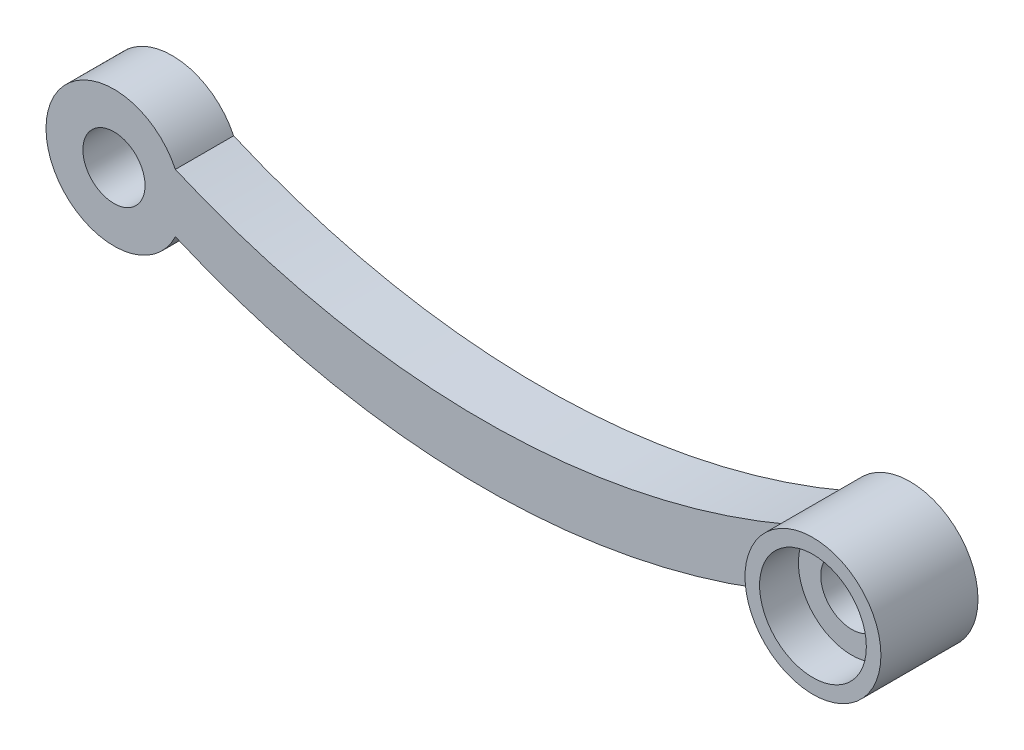
SolidWorks part; units mm, degrees
ref_plane "Front Plane" through (0, 0, 0) normal (0, 0, 1) x (1, 0, 0)
ref_plane "Top Plane" through (0, 0, 0) normal (0, 1, 0) x (1, 0, 0)
ref_plane "Right Plane" through (0, 0, 0) normal (1, 0, 0) x (0, 0, -1)
sketch "Sketch2" plane through (0, 0, 0) normal (0, 0, 1) x (1, 0, 0)
  line L0 (-19, 0) -> (-11.7639, 0) construction
  line L1 (-19, 3.5) -> (19, 3.5) construction
  line L2 (-19, -3.5) -> (19, -3.5) construction
  line L3 (0, 0) -> (0, -3.5) construction
  line L5 (15.8377, -1.5) -> (15.8377, 1.5) construction
  line L7 (-15.8377, -1.5) -> (-15.8377, 1.5) construction
  line L9 (15.8377, 1.5) -> (8.6603, 0.8202) construction
  line L10 (11.7639, 0) -> (19, 0) construction
  line L11 (-8.6603, 0.8202) -> (-15.8377, 1.5) construction
  arc A0 (-19, 3.5) -> (-19, -3.5) centre (-19, 0) ccw construction
  arc A1 (19, -3.5) -> (19, 3.5) centre (19, 0) ccw construction
  arc A2 (-15.8377, 1.5) -> (-15.8377, -1.5) centre (-19, 0) ccw
  circle A3 centre (-19, 0) radius 1.6
  circle A4 centre (19, 0) radius 1.6
  arc A5 (15.8377, 1.5) -> (15.8377, -1.5) centre (19, 0) cw
  arc A8 (-15.8377, -1.5) -> (15.8377, -1.5) centre (0, 35.231) ccw
  arc A9 (-15.8377, 1.5) -> (15.8377, 1.5) centre (0, 38.231) ccw
  point P2 (0, 0)
  dimension "D3" = 3.2
  dimension "D1" = 38
  dimension "D2" = 7
extrude "Boss-Extrude1" add sketch "Sketch2" along normal blind 3
sketch "Sketch3" plane through (0, 0, 3) normal (0, 0, 1) x (1, 0, 0)
  circle A0 centre (19, 0) radius 3.5
  circle A1 centre (19, 0) radius 2.75
  dimension "D1" = 7
  dimension "D2" = 5.5
extrude "Boss-Extrude2" add sketch "Sketch3" along normal blind 2
